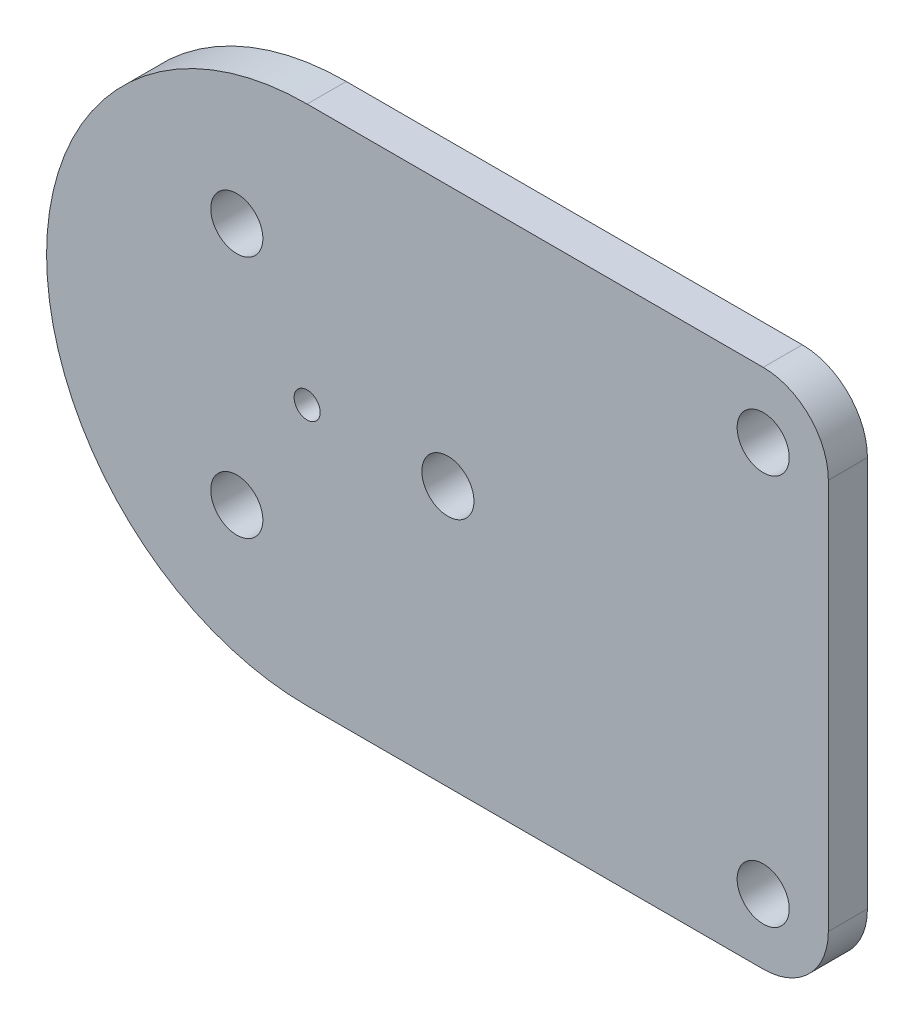
SolidWorks part; units mm, degrees
ref_plane "Ebene vorne" through (0, 0, 0) normal (0, 0, 1) x (1, 0, 0)
ref_plane "Ebene oben" through (0, 0, 0) normal (0, 1, 0) x (1, 0, 0)
ref_plane "Ebene rechts" through (0, 0, 0) normal (1, 0, 0) x (0, 0, -1)
sketch "Skizze1" plane through (0, 0, 0) normal (0, 0, 1) x (1, 0, 0)
  line L0 (0, 20) -> (40, 20)
  line L1 (0, -20) -> (40, -20)
  line L2 (40, 20) -> (40, -20)
  line L3 (0, 0) -> (40, 0) construction
  circle A0 centre (0, 0) radius 20
  circle A1 centre (0, 0) radius 1
  circle A3 centre (35, -15) radius 2
  circle A4 centre (35, 15) radius 2
  dimension "D1" = 40
  dimension "D2" = 2
  dimension "D8" = 4
  dimension "D3" = 40
  dimension "D6" = 5
  dimension "D7" = 5
extrude "Aufsatz-Linear austragen1" add sketch "Skizze1" along normal blind 3
sketch "Skizze2" plane through (0, 0, 0) normal (0, 0, -1) x (-1, 0, 0)
  line L0 (0, 0) -> (-10.8, 0) construction
  circle A0 centre (-10.8, 0) radius 2
  circle A1 centre (5.4, 9.3531) radius 2
  circle A2 centre (5.4, -9.3531) radius 2
  point P11 (0, 0)
  dimension "D2" = 4
  dimension "D1" = 10.8
  dimension "D3" = 3
extrude "Schnitt-Linear austragen1" cut sketch "Skizze2" against normal through all
fillet "Verrundung1" radius 5 2 edges at (40, -20, 1.5) (40, 20, 1.5)
